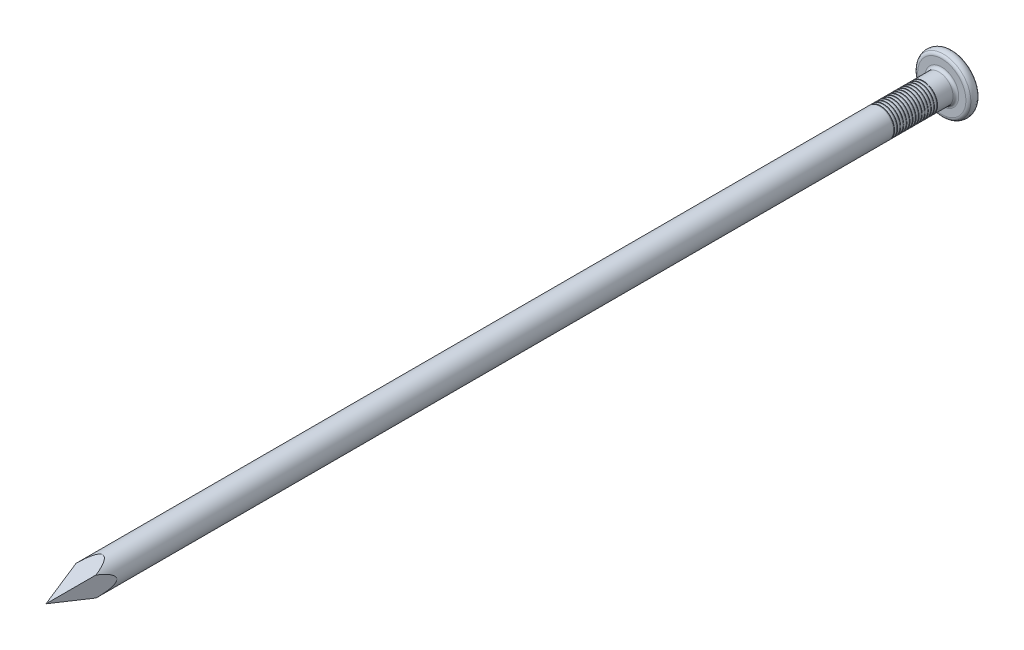
SolidWorks part; units mm, degrees
ref_plane "Front Plane" through (0, 0, 0) normal (0, 0, 1) x (1, 0, 0)
ref_plane "Top Plane" through (0, 0, 0) normal (0, 1, 0) x (1, 0, 0)
ref_plane "Right Plane" through (0, 0, 0) normal (1, 0, 0) x (0, 0, -1)
sketch "Sketch1" plane through (0, 0, 0) normal (1, 0, 0) x (0, 0, -1)
  line L0 (-152.4, 0) -> (152.4, 0) construction
  line L1 (-152.4, 4.7625) -> (-152.4, -4.7625) construction
  line L2 (152.4, -9.525) -> (152.4, 9.525) construction
  line L3 (0, 0) -> (0, 9.525) construction
  point P3 (101.6, 0)
  point P4 (0, 0)
  point P8 (-152.4, 0)
  point P10 (-101.6, 0)
  point P11 (152.4, 0)
  dimension "Length" = 304.8
  dimension "Shank Diameter" = 9.525
  dimension "Head Diameter" = 19.05
  dimension "D1" = 50.8
sketch "Sketch2" plane through (0, 0, 0) normal (1, 0, 0) x (0, 0, -1)
  line L1 (-133.35, -4.7625) -> (152.4, -4.7625)
  line L2 (-152.4, 0) -> (152.4, 0) construction
  line L3 (-152.4, 0) -> (152.4, 0)
  line L4 (152.4, 0) -> (152.4, -4.7625)
  line L5 (-152.4, 0) -> (-152.4, -4.7625)
  line L7 (-152.4, -4.7625) -> (-133.35, -4.7625)
  line L8 (-133.35, -4.7625) -> (-152.4, -0.0025) construction
  line L9 (152.4, -9.525) -> (152.4, 9.525) construction
  point P2 (144.4625, 0)
  dimension "D1" = 19.05
  dimension "D2" = 0.0025
  dimension "D3" = 7.9375
revolve "Revolve1" add sketch "Sketch2" angle 360 about L3
sketch "Sketch3" plane through (0, 0, 0) normal (1, 0, 0) x (0, 0, -1)
  line L0 (-152.4, -0.0025) -> (-133.35, -4.7625)
  line L1 (-133.35, -4.7625) -> (-152.4, -4.7625)
  line L2 (-152.4, -4.7625) -> (-152.4, -0.0025)
  line L3 (-152.4, 0) -> (152.4, 0) construction
  line L4 (-152.4, 0) -> (152.4, 0) construction
extrude "Cut-Extrude1" cut sketch "Sketch3" against normal through all both and the other way through all
pattern_circular "CirPattern1" count 4 over 360 about axis through (0, 0, 0) along (0, 0, 1) of "Cut-Extrude1"
sketch "Sketch5" plane through (0, 0, 0) normal (1, 0, 0) x (0, 0, -1)
  line L0 (152.4, -9.525) -> (152.4, 9.525) construction
  line L1 (152.4, 0) -> (152.4, 9.525) construction
  line L2 (148.8281, 9.525) -> (148.8281, 0) construction
  line L3 (-152.4, 0) -> (152.4, 0) construction
  line L5 (148.8281, 9.525) -> (152.4, 9.525) construction
  line L6 (152.4, 0) -> (0, 0) construction
  line L7 (148.8281, 0) -> (152.4, 0)
  line L8 (148.8281, 0) -> (148.8281, 8.105)
  line L9 (152.4, 0) -> (152.4, 8.105)
  arc A0 (149.4173, 9.1771) -> (151.8108, 9.1771) centre (150.6141, 7.2926) cw
  arc A1 (152.4, 8.105) -> (151.8108, 9.1771) centre (151.13, 8.105) ccw
  arc A2 (148.8281, 8.105) -> (149.4173, 9.1771) centre (150.0981, 8.105) cw
  point P2 (143.1925, 0)
  point P3 (-151.13, 0)
  point P12 (148.8281, 9.525)
  point P20 (152.4, 8.632)
  point P23 (148.8281, 8.632)
  dimension "D1" = 3.5719
  dimension "D2" = 1.27
  dimension "D4" = 294.3225
  dimension "D5" = 0.893
  dimension "D3" = 1.27
revolve "Revolve2" add sketch "Sketch5" angle 360 about L6
ref_plane "Plane1" through (4.7625, 0, 0) normal (1, 0, 0) x (0, 0, -1)
sketch "Sketch6" plane through (4.7625, 0, 0) normal (1, 0, 0) x (0, 0, -1)
  line L0 (-152.4, 0) -> (152.4, 0) construction
  line L1 (-152.4, 0) -> (152.4, 0) construction
  line L8 (140.2556, -9.525) -> (140.5731, -9.525)
  line L41 (142.3194, -9.525) -> (142.6369, -9.525)
  line L42 (142.3194, -9.525) -> (142.3194, 9.525)
  line L43 (142.3194, 9.525) -> (142.6369, 9.525)
  line L44 (142.6369, -9.525) -> (142.6369, 9.525)
  line L45 (142.3194, -9.525) -> (142.6369, 9.525) construction
  line L46 (142.3194, 9.525) -> (142.6369, -9.525) construction
  line L47 (141.2875, -9.525) -> (141.605, -9.525)
  line L48 (141.605, -9.525) -> (141.605, 9.525)
  line L49 (141.2875, -9.525) -> (141.2875, 9.525)
  line L50 (141.2875, 9.525) -> (141.605, 9.525)
  line L52 (140.5731, -9.525) -> (140.5731, 9.525)
  line L53 (140.2556, -9.525) -> (140.2556, 9.525)
  line L54 (140.2556, 9.525) -> (140.5731, 9.525)
  line L55 (139.2238, -9.525) -> (139.5413, -9.525)
  line L56 (139.5413, -9.525) -> (139.5413, 9.525)
  line L57 (139.2238, -9.525) -> (139.2238, 9.525)
  line L58 (139.2238, 9.525) -> (139.5413, 9.525)
  line L59 (138.1919, -9.525) -> (138.5094, -9.525)
  line L60 (138.5094, -9.525) -> (138.5094, 9.525)
  line L61 (138.1919, -9.525) -> (138.1919, 9.525)
  line L62 (138.1919, 9.525) -> (138.5094, 9.525)
  line L63 (137.16, -9.525) -> (137.4775, -9.525)
  line L64 (137.4775, -9.525) -> (137.4775, 9.525)
  line L65 (137.16, -9.525) -> (137.16, 9.525)
  line L66 (137.16, 9.525) -> (137.4775, 9.525)
  line L67 (136.1281, -9.525) -> (136.4456, -9.525)
  line L68 (136.4456, -9.525) -> (136.4456, 9.525)
  line L69 (136.1281, -9.525) -> (136.1281, 9.525)
  line L70 (136.1281, 9.525) -> (136.4456, 9.525)
  line L71 (135.0963, -9.525) -> (135.4138, -9.525)
  line L72 (135.4138, -9.525) -> (135.4138, 9.525)
  line L73 (135.0963, -9.525) -> (135.0963, 9.525)
  line L74 (135.0963, 9.525) -> (135.4138, 9.525)
  line L75 (134.0644, -9.525) -> (134.3819, -9.525)
  line L76 (134.3819, -9.525) -> (134.3819, 9.525)
  line L77 (134.0644, -9.525) -> (134.0644, 9.525)
  line L78 (134.0644, 9.525) -> (134.3819, 9.525)
  line L79 (133.0325, -9.525) -> (133.35, -9.525)
  line L80 (133.35, -9.525) -> (133.35, 9.525)
  line L81 (133.0325, -9.525) -> (133.0325, 9.525)
  line L82 (133.0325, 9.525) -> (133.35, 9.525)
  line L83 (132.0006, -9.525) -> (132.3181, -9.525)
  line L84 (132.3181, -9.525) -> (132.3181, 9.525)
  line L85 (132.0006, -9.525) -> (132.0006, 9.525)
  line L86 (132.0006, 9.525) -> (132.3181, 9.525)
  line L87 (130.9688, -9.525) -> (131.2863, -9.525)
  line L88 (131.2863, -9.525) -> (131.2863, 9.525)
  line L89 (130.9688, -9.525) -> (130.9688, 9.525)
  line L90 (130.9688, 9.525) -> (131.2863, 9.525)
  line L91 (148.8281, 8.105) -> (148.8281, -8.105) construction
  line L92 (148.8281, 9.525) -> (152.4, 9.525) construction
  line L93 (129.9369, -9.525) -> (130.2544, -9.525)
  line L94 (130.2544, -9.525) -> (130.2544, 9.525)
  line L95 (129.9369, -9.525) -> (129.9369, 9.525)
  line L96 (129.9369, 9.525) -> (130.2544, 9.525)
  line L97 (128.905, -9.525) -> (129.2225, -9.525)
  line L98 (129.2225, -9.525) -> (129.2225, 9.525)
  line L99 (128.905, -9.525) -> (128.905, 9.525)
  line L100 (128.905, 9.525) -> (129.2225, 9.525)
  line L101 (127.8731, -9.525) -> (128.1906, -9.525)
  line L102 (128.1906, -9.525) -> (128.1906, 9.525)
  line L103 (127.8731, -9.525) -> (127.8731, 9.525)
  line L104 (127.8731, 9.525) -> (128.1906, 9.525)
  point P15 (142.4781, 0)
  dimension "D7" = 0.7144
  dimension "D1" = 0.3175
  dimension "D5" = 6.35
  dimension "D6" = 15
extrude "Cut-Extrude3" cut sketch "Sketch6" against normal through all
sketch "Sketch7" plane through (0, 0, -148.8281) normal (0, 0, 1) x (1, 0, 0)
  circle A0 centre (0, 0) radius 4.6355
  circle A1 centre (0, 0) radius 4.7625 construction
  dimension "D1" = 0.127
extrude "Boss-Extrude1" add sketch "Sketch7" along normal up to vertex (13.4144 mm away)
fillet "Fillet1" radius 0.9525 1 edges at (-4.7625, 0, -148.8281)
equation "\"D1@Sketch2\"=\"Shank Diameter@Sketch1\"*2"
equation "\"D1@Sketch5\"=\"Head Diameter@Sketch1\" * 0.1875"
equation "\"D7@Sketch6\"=\"D1@Sketch6\"*2.25"
equation "\"D5@Sketch5\"=\"D1@Sketch5\"/4"
equation "\"D1@Fillet1\"=\"Head Diameter@Sketch1\"*0.05"
